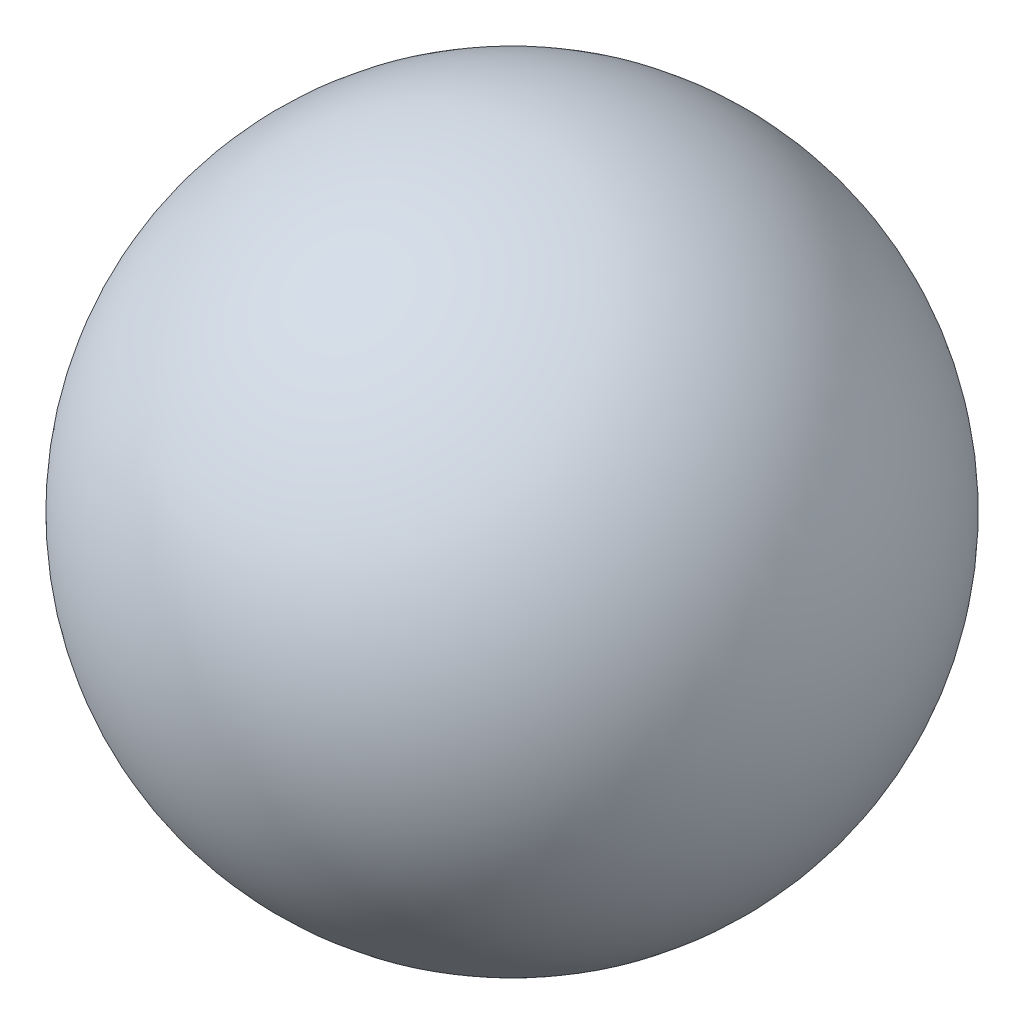
SolidWorks part; units mm, degrees
ref_plane "Front Plane" through (0, 0, 0) normal (0, 0, 1) x (1, 0, 0)
ref_plane "Top Plane" through (0, 0, 0) normal (0, 1, 0) x (1, 0, 0)
ref_plane "Right Plane" through (0, 0, 0) normal (1, 0, 0) x (0, 0, -1)
sketch "Sketch2" plane through (0, 0, 0) normal (0, 0, 1) x (1, 0, 0)
  line L0 (0, 12) -> (0, -12) construction
  line L1 (0, 12) -> (0, -12)
  arc A0 (0, 12) -> (0, -12) centre (0, 0) ccw
revolve "Revolve4" add sketch "Sketch2" angle 360 about L0
